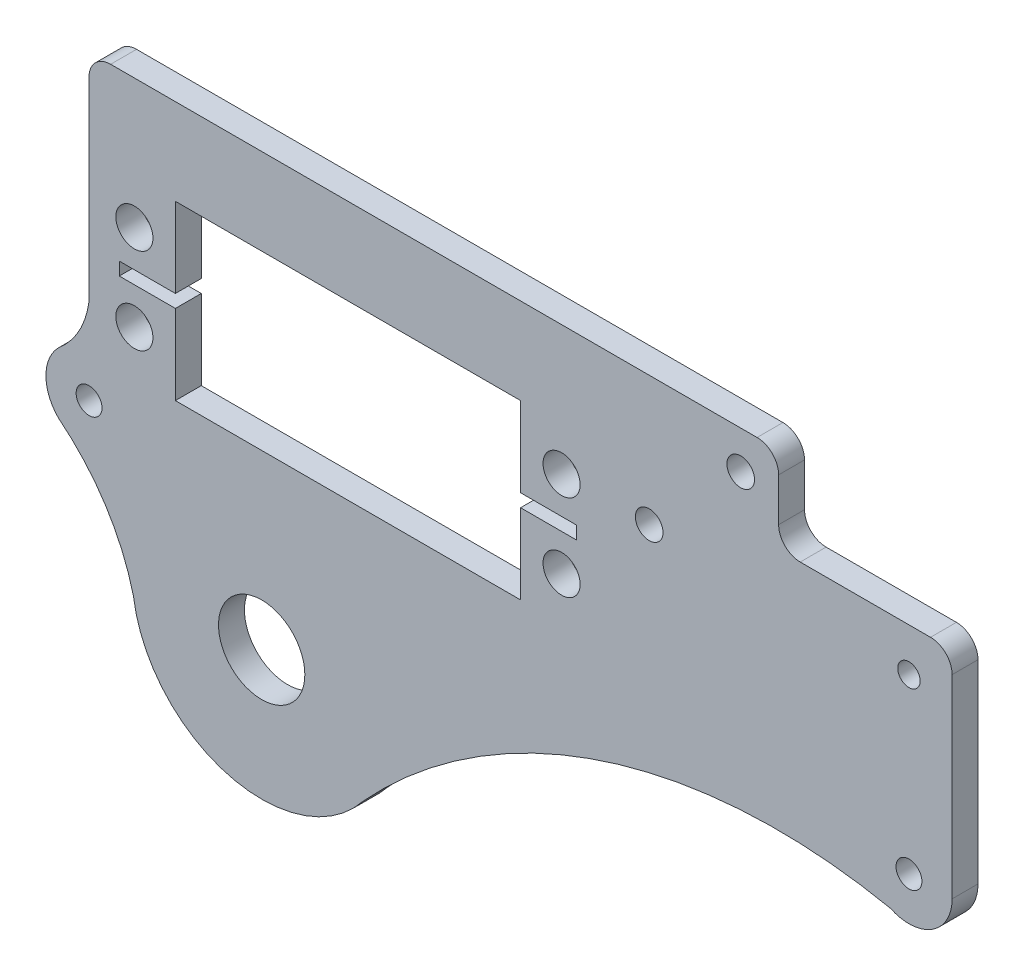
SolidWorks part; units mm, degrees
material "ｱｸﾘﾙ (中-上級の耐衝撃性)"
ref_plane "正面" through (0, 0, 0) normal (0, 0, 1) x (1, 0, 0)
ref_plane "平面" through (0, 0, 0) normal (0, 1, 0) x (1, 0, 0)
ref_plane "右側面" through (0, 0, 0) normal (1, 0, 0) x (0, 0, -1)
sketch "ｽｹｯﾁ1" plane through (0, 0, 0) normal (0, 0, 1) x (1, 0, 0)
  line L0 (0, 50) -> (100, 50) construction
  line L3 (0, 60) -> (100, 60)
  line L4 (100, 50) -> (100, 60)
  line L5 (10, 60) -> (50, 60)
  line L6 (10, 60) -> (10, 40)
  line L7 (10, 40) -> (50, 40)
  line L8 (50, 60) -> (50, 40)
  line L9 (30, 60) -> (30, 40) construction
  line L10 (100, 50) -> (100, 0)
  line L13 (0, 0) -> (100, 0)
  line L14 (0, 60) -> (0, 0)
  line L15 (20, 50) -> (20, 0) construction
  circle A0 centre (5.25, 55) radius 2.15
  circle A1 centre (5.25, 45) radius 2.15
  circle A2 centre (54.75, 55) radius 2.15
  circle A3 centre (54.75, 45) radius 2.15
  circle A4 centre (20, 20) radius 5
  dimension "D4" = 4.3
  dimension "D5" = 4.75
  dimension "D6" = 5
  dimension "D10" = 10
  dimension "D12" = 30
  dimension "D1" = 10
  dimension "D2" = 20
  dimension "D3" = 30
  dimension "D7" = 60
  dimension "D8" = 40
  dimension "D9" = 100
  dimension "D11" = 10
extrude "ﾎﾞｽ - 押し出し1" add sketch "ｽｹｯﾁ1" along normal blind 3
sketch "ｽｹｯﾁ2" plane through (0, 0, 3) normal (0, 0, 1) x (1, 0, 0)
  line L1 (100, 60) -> (100, 0) construction
  line L2 (50, 60) -> (100, 60) construction
  circle A1 centre (95, 35) radius 1.5
  dimension "D1" = 3
  dimension "D4" = 5
  dimension "D5" = 25
extrude "ｶｯﾄ - 押し出し1" cut sketch "ｽｹｯﾁ2" against normal through all
sketch "ｽｹｯﾁ4" plane through (0, 0, 3) normal (0, 0, 1) x (1, 0, 0)
  line L0 (0, 60) -> (0, 0) construction
  line L1 (5.25, 45) -> (1.5377, 41.2877) construction
  line L2 (5.25, 45) -> (5.25, 39.75) construction
  line L3 (20, 20) -> (6.1418, 25.7403) construction
  line L4 (5, 20) -> (20, 20) construction
  line L5 (20, 20) -> (30.6066, 9.3934) construction
  line L6 (95, 35) -> (95, 30) construction
  circle A0 centre (20, 20) radius 15
  circle A1 centre (95, 35) radius 5
  circle A2 centre (20, 20) radius 5 construction
  circle A3 centre (5.25, 45) radius 5.25
  arc A4 (1.5377, 41.2877) -> (6.1418, 25.7403) centre (-9.3863, 29.5973) cw
  arc A5 (30.6066, 9.3934) -> (95, 30) centre (79.7243, -33.1795) cw
  line M12 (0, 60) -> (0, 0)
  line M13 (0, 0) -> (100, 0)
  line M14 (100, 0) -> (100, 60)
  dimension "D1" = 10
  dimension "D2" = 10
  dimension "D5" = 16
  dimension "D6" = 135
  dimension "D7" = 65
  dimension "D3" = 45
  dimension "D4" = 22.5
extrude "ｶｯﾄ - 押し出し3" cut sketch "ｽｹｯﾁ4" against normal through all contours A5 A0 A4 A3 A1 M12 M13 M14
sketch "ｽｹｯﾁ5" plane through (0, 0, 3) normal (0, 0, 1) x (1, 0, 0)
  line L0 (0, 35) -> (-5, 35) construction
  line L1 (0, 35) -> (-3.5355, 38.5355) construction
  line L2 (0, 35) -> (-3.5355, 31.4645) construction
  line L3 (10, 50) -> (50, 50) construction
  line L4 (10, 60) -> (10, 40) construction
  line L5 (50, 60) -> (50, 40) construction
  circle A0 centre (0, 35) radius 5
  arc A1 (-3.5355, 38.5355) -> (0, 45) centre (-9.9242, 46.2287) ccw
  arc A2 (-3.5355, 31.4645) -> (5.1339, 18) centre (-19.1132, 11.9111) cw
  circle A3 centre (0, 35) radius 1.5
  arc A5 (6.1418, 25.7403) -> (31.7611, 10.69) centre (20, 20) ccw construction
  circle A6 centre (20, 20) radius 5 construction
  point P14 (20, 50)
  arc M16 (0, 45) -> (1.7318, 41.1032) centre (5.25, 45) ccw
  arc M17 (1.7318, 41.1032) -> (6.1418, 25.7403) centre (-9.3863, 29.5973) cw
  arc M18 (6.1418, 25.7403) -> (31.7611, 10.69) centre (20, 20) ccw
  dimension "D1" = 10
  dimension "D3" = 10
  dimension "D4" = 3
  dimension "D6" = 25
  dimension "D8" = 25
  dimension "D2" = 45
  dimension "D5" = 45
  dimension "D7" = 18
  dimension "D9" = 10
  dimension "D10" = 25
extrude "ﾎﾞｽ - 押し出し3" add sketch "ｽｹｯﾁ5" against normal through all contours A0 A2 A1 A3 | A0 A2 A1 M18 M17 M16
sketch "ｽｹｯﾁ6" plane through (0, 0, 3) normal (0, 0, 1) x (1, 0, 0)
  line L0 (95, 60) -> (95, 30) construction
  line L1 (50, 60) -> (100, 60) construction
  line L2 (100, 60) -> (100, 35) construction
  arc A0 (92.8666, 30.478) -> (31.7611, 10.69) centre (79.7243, -33.1795) ccw construction
  circle A1 centre (95, 45) radius 1.3
  circle A2 centre (95, 55) radius 1.3
  dimension "D2" = 2.6
  dimension "D3" = 5
  dimension "D4" = 15
  dimension "D1" = 5
extrude "ｶｯﾄ - 押し出し4" cut sketch "ｽｹｯﾁ6" against normal through all contours A2 L0 | L0 A2
sketch "ｽｹｯﾁ7" plane through (0, 0, 3) normal (0, 0, 1) x (1, 0, 0)
  line L0 (90, 60) -> (140, 110)
  line L1 (90, 39.1533) -> (100, 39.1533) construction
  line L2 (90, 39.1533) -> (90, 60)
  line L3 (90, 60) -> (100, 60)
  line L4 (100, 39.1533) -> (100, 60)
  line L5 (140, 110) -> (170, 110)
  line L6 (140, 110) -> (140, 100)
  line L7 (140, 100) -> (170, 100)
  line L8 (170, 110) -> (170, 100)
  line L9 (100, 60) -> (140, 100)
  line L10 (95, 60) -> (95, 39.1533) construction
  line L11 (115, 85) -> (120, 80) construction
  line L12 (140, 105) -> (170, 105) construction
  line L13 (90, 60) -> (90, 110)
  line L14 (90, 110) -> (140, 110)
  line L15 (110, 110) -> (90, 90)
  line L16 (90, 90) -> (60, 60)
  line L17 (60, 60) -> (90, 60)
  line L18 (70, 60) -> (120, 110)
  line L19 (60, 60) -> (70, 60)
  line L20 (60, 60) -> (60, 50)
  line L21 (60, 50) -> (70, 50)
  line L22 (70, 60) -> (70, 50)
  line L23 (64.9, 50) -> (64.9, 60) construction
  line L24 (96, 86) -> (96, 66)
  line L25 (134, 104) -> (114, 104)
  circle A0 centre (95, 35) radius 5
  circle A1 centre (95, 35) radius 6.5
  circle A2 centre (95, 55) radius 1.6
  circle A3 centre (95, 45) radius 1.6
  circle A4 centre (150, 105) radius 1.3
  circle A5 centre (160, 105) radius 1.3
  circle A6 centre (64.9, 55) radius 1.6
  circle A8 centre (95, 35) radius 1.5
  dimension "D1" = 10
  dimension "D2" = 13
  dimension "D8" = 3.2
  dimension "D11" = 2.6
  dimension "D17" = 3.2
  dimension "D20" = 3
  dimension "D3" = 25
  dimension "D4" = 30
  dimension "D5" = 10
  dimension "D6" = 40
  dimension "D7" = 40
  dimension "D9" = 5
  dimension "D10" = 15
  dimension "D12" = 10
  dimension "D13" = 20
  dimension "D14" = 45
  dimension "D15" = 20
  dimension "D16" = 10
  dimension "D18" = 6
  dimension "D19" = 6
  dimension "D21" = 5.1
extrude "ｶｯﾄ - 押し出し6" cut sketch "ｽｹｯﾁ7" against normal through all contours A6
sketch "ｽｹｯﾁ8" plane through (0, 0, 3) normal (0, 0, 1) x (1, 0, 0)
  line L0 (10, 50) -> (50, 50) construction
  line L1 (10, 60) -> (10, 40) construction
  line L2 (50, 60) -> (50, 40) construction
  line L4 (3.5, 49.25) -> (56.5, 49.25)
  line L5 (3.5, 49.25) -> (3.5, 50.75)
  line L6 (3.5, 50.75) -> (56.5, 50.75)
  line L7 (56.5, 49.25) -> (56.5, 50.75)
  line L8 (3.5, 49.25) -> (56.5, 50.75) construction
  line L9 (3.5, 50.75) -> (56.5, 49.25) construction
  point P6 (30, 50)
  dimension "D1" = 1.5
  dimension "D2" = 53
extrude "ｶｯﾄ - 押し出し7" cut sketch "ｽｹｯﾁ8" against normal through all
sketch "ｽｹｯﾁ9" plane through (0, 0, 3) normal (0, 0, 1) x (1, 0, 0)
  line L0 (79.9, 70) -> (64.9, 55) construction
  line L1 (0, 60) -> (79.9, 60)
  line L2 (0, 60) -> (0, 70)
  line L3 (0, 70) -> (79.9, 70)
  line L4 (79.9, 60) -> (79.9, 70)
  circle A0 centre (75.5066, 65.6066) radius 1.6
  circle A1 centre (64.9, 55) radius 1.6 construction
  dimension "D3" = 15
  dimension "D1" = 10
  dimension "D2" = 45
extrude "ﾎﾞｽ - 押し出し4" add sketch "ｽｹｯﾁ9" against normal through all
fillet "ﾌｨﾚｯﾄ1" radius 2.5 4 edges at (0, 70, 1.5) (100, 60, 1.5) (79.9, 60, 1.5) (79.9, 70, 1.5)
